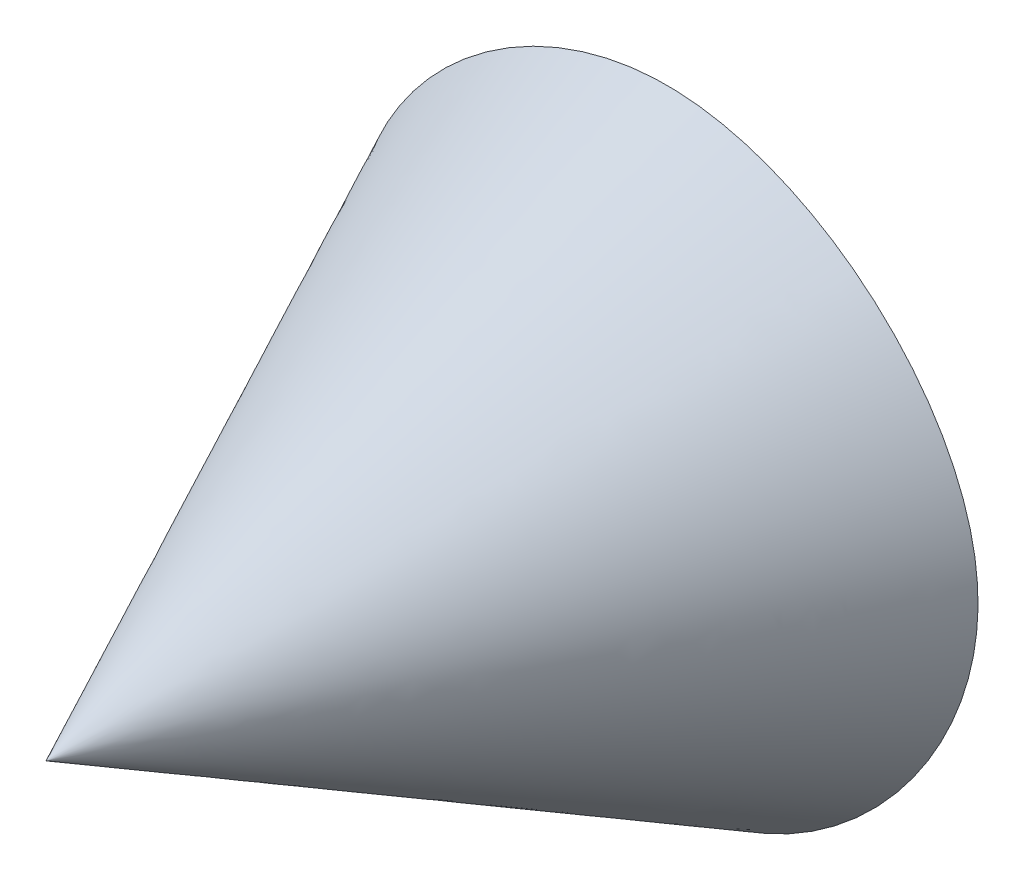
SolidWorks part; units mm, degrees
other "Camera2"
other "Markup1" [suppressed]
sketch "Sketch9" [suppressed] plane through (62.8636, 53.3376, 108.883) normal (1, 0, 0) x (0, 0, 1)
sketch "Sketch10" plane through (62.8636, 53.3376, 108.883) normal (1, 0, 0) x (0, 0, 1)
sketch "Sketch11" [suppressed] plane through (62.8636, 53.3376, 109.299) normal (1, 0, 0) x (0, 0, 1)
sketch "Sketch12" [suppressed] plane through (54.313, 46.6008, 109.299) normal (1, 0, 0) x (0, 0, 1)
sketch "Sketch13" plane through (62.8636, 53.3376, 108.883) normal (1, 0, 0) x (0, 0, 1)
ref_plane "Front Plane" through (0, 0, 0) normal (0, 0, 1) x (1, 0, 0)
ref_plane "Top Plane" through (0, 0, 0) normal (0, 1, 0) x (1, 0, 0)
ref_plane "Right Plane" through (0, 0, 0) normal (1, 0, 0) x (0, 0, -1)
sketch "Sketch1" plane through (0, 0, 0) normal (1, 0, 0) x (0, 0, -1)
  line L0 (0, 0) -> (-68.9166, 0) construction
  line L1 (-2.1532, 12.2116) -> (-107.6384, -18.9795)
  line L2 (-107.6384, -18.9795) -> (0, 0)
  line L3 (0, 0) -> (-2.1532, 12.2116)
  point P8 (-2.1532, 12.2116)
  point P11 (0, 0)
  dimension "D1" = 12.4
  dimension "D2" = 110
  dimension "pitch" = 10
ref_plane "Plane1" through (0, 0, 0) normal (0, 0.9848, 0.1736) x (1, 0, 0)
sketch "Sketch2" plane through (0, 0, 0) normal (0, 0.9848, 0.1736) x (1, 0, 0)
  line L0 (0, -109.2989) -> (-34, 0)
  line L1 (0, -109.2989) -> (0, 0) construction
  line L2 (-34, 0) -> (34, 0)
  line L3 (34, 0) -> (0, -109.2989)
  point P8 (0, 0)
  dimension "D1" = 68
sketch "Sketch3" plane through (0, 0, 0) normal (1, 0, 0) x (0, 0, -1)
  point P0 (-2.1532, 12.2116)
loft "Loft1" add profiles "Sketch3", "Sketch2"
sketch "Sketch4" plane through (0, 0, 0) normal (1, 0, 0) x (0, 0, -1)
  line L0 (-107.6384, -18.9795) -> (0, 28.7192)
  line L1 (-107.6384, -18.9795) -> (0, -78.8903)
  line L2 (200000, 0) -> (-200068.9166, 0) construction
  dimension "top_angle" = 29.1
  dimension "bottom_angle" = 23.9
ref_plane "Plane2" through (0, -18.9795, 0) normal (0, 1, 0) x (1, 0, 0)
sketch "Sketch6" plane through (0, -18.9795, 0) normal (0, 1, 0) x (1, 0, 0)
  line L0 (0, -107.6384) -> (53.9013, 0)
  line L1 (0, -107.6384) -> (-53.9013, 0)
  line L2 (0, -2.1532) -> (0, -107.6384) construction
  line L3 (0, -107.6384) -> (0, 0) construction
  dimension "left" = 26.6
  dimension "right" = 26.6
sketch "Sketch7" plane through (0, 0, 0) normal (0, 0, 1) x (1, 0, 0)
  line L0 (0, -18.9795) -> (0, -78.8903) construction
  line L1 (59.7443, -18.9795) -> (-59.7443, -18.9795) construction
  line L2 (0, -18.9795) -> (0, 28.7192) construction
  line L3 (0, -18.9795) -> (53.9013, -18.9795) construction
  spline S0 degree 3 poles (81.0817, -18.9294) (0, -110.5634) (-81.0817, -18.9294) (0, 51.1984) (81.0817, -18.9294) (0, -110.5634) (-81.0817, -18.9294) knots -0.735885 -0.5 -0.264115 0 0.264115 0.5 0.735885 1 1.264115 1.5 1.735885 only from (0, -78.8903) to (0, -78.8903)
sketch "Sketch8" plane through (0, -18.9795, 0) normal (0, 1, 0) x (1, 0, 0)
  point P0 (0, -107.6384)
surface "Surface-Loft1"
